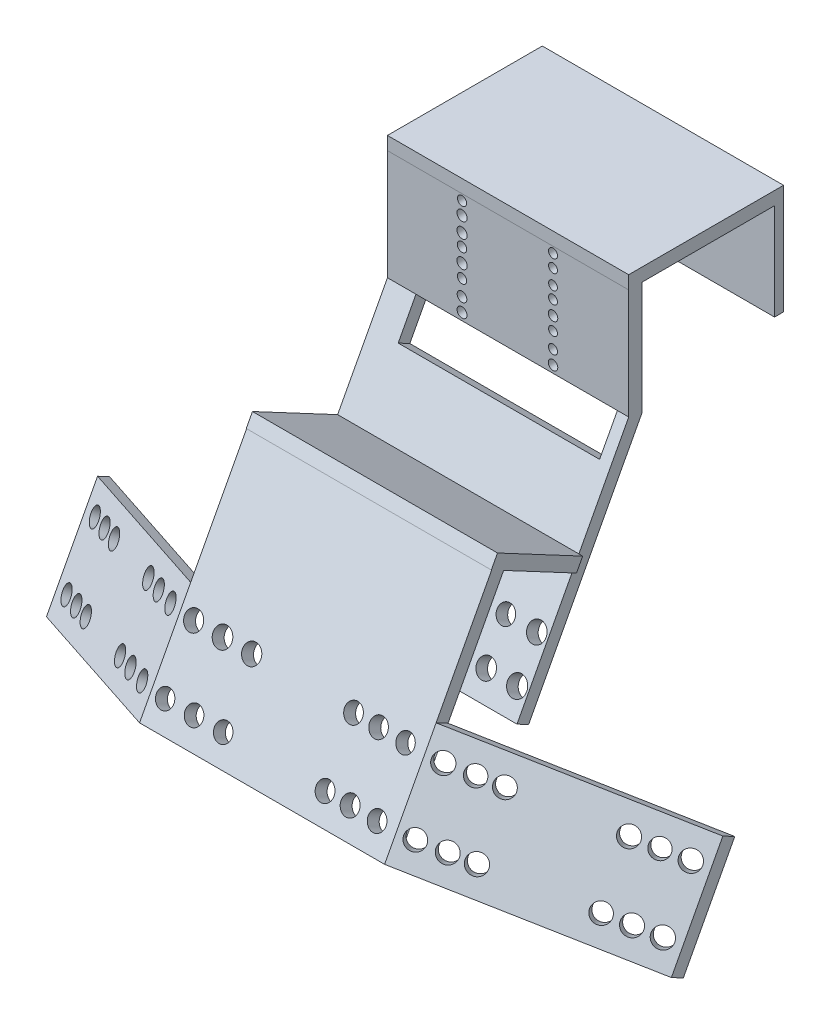
SolidWorks part; units mm, degrees
ref_plane "Plan de face" through (0, 0, 0) normal (0, 0, 1) x (1, 0, 0)
ref_plane "Plan de dessus" through (0, 0, 0) normal (0, 1, 0) x (1, 0, 0)
ref_plane "Plan de droite" through (0, 0, 0) normal (1, 0, 0) x (0, 0, -1)
sketch "Esquisse1" plane through (0, 0, 0) normal (0, 0, 1) x (1, 0, 0)
  line L1 (-52.422, 30.1085) -> (2.578, 30.1085)
  line L2 (-52.422, 30.1085) -> (-52.422, 4.2593)
  line L3 (-52.422, 4.2593) -> (2.578, 4.2593)
  line L4 (2.578, 30.1085) -> (2.578, 4.2593)
extrude "Boss.-Extru.1" add sketch "Esquisse1" along normal blind 3
ref_plane "Plan1" through (0, 0.9388, 1.7655) normal (0, -0.4695, -0.8829) x (1, 0, 0)
sketch "Esquisse2" plane through (0, 0.9388, 1.7655) normal (0, -0.4695, -0.8829) x (1, 0, 0)
  line L1 (-52.422, -3.7607) -> (2.578, -3.7607)
  line L2 (-52.422, -3.7607) -> (-52.422, 51.2393)
  line L3 (-52.422, 51.2393) -> (2.578, 51.2393)
  line L4 (2.578, -3.7607) -> (2.578, 51.2393)
  dimension "D1" = 55
extrude "Boss.-Extru.2" add sketch "Esquisse2" against normal blind 3
ref_plane "Plan12" through (0, 30.1085, 0) normal (0, 1, 0) x (1, 0, 0)
sketch "Esquisse16" plane through (0, 30.1085, 0) normal (0, 1, 0) x (1, 0, 0)
  line L0 (-52.422, -3) -> (-52.422, 0) construction
  line L1 (-52.422, -3.0047) -> (2.578, -3.0047)
  line L2 (-52.422, -3.0047) -> (-52.422, 32.3024)
  line L3 (-52.422, 32.3024) -> (2.578, 32.3024)
  line L4 (2.578, -3.0047) -> (2.578, 32.3024)
extrude "Boss.-Extru.15" add sketch "Esquisse16" along normal blind 3
sketch "Esquisse19" plane through (0, 0.9388, 1.7655) normal (0, -0.4695, -0.8829) x (1, 0, 0)
  line L0 (-51.2999, 51.5904) -> (-51.2999, 21.0995)
ref_plane "Plan15" through (0, 2.3472, 4.4144) normal (0, 0.4695, 0.8829) x (1, 0, 0)
sketch "Esquisse20" plane through (0, 2.3472, 4.4144) normal (0, 0.4695, 0.8829) x (1, 0, 0)
  line L0 (-52.422, -21.1686) -> (2.578, -21.1686)
  line L1 (-52.422, -51.2393) -> (-52.422, 3.0127) construction
  line L2 (2.578, 3.0127) -> (2.578, -51.2393) construction
ref_plane "Plan16" through (0, -18.6908, 9.9381) normal (0, -0.8829, 0.4695) x (1, 0, 0)
sketch "Esquisse21" plane through (0, -18.6908, 9.9381) normal (0, -0.8829, 0.4695) x (1, 0, 0)
  line L1 (-52.422, 4.9996) -> (3.4425, 4.9996)
  line L2 (-52.422, 4.9996) -> (-52.422, 26.9996)
  line L3 (-52.422, 26.9996) -> (3.4425, 26.9996)
  line L4 (3.4425, 4.9996) -> (3.4425, 26.9996)
  dimension "D1" = 22
extrude "Boss.-Extru.17" add sketch "Esquisse21" along normal blind 3
ref_plane "Plan17" through (0, 12.6755, 23.8392) normal (0, 0.4695, 0.8829) x (1, 0, 0)
sketch "Esquisse25" plane through (0, 2.3472, 4.4144) normal (0, 0.4695, 0.8829) x (1, 0, 0)
  line L1 (0, 3.4498) -> (-45.9174, 3.4498)
  line L2 (0, 3.4498) -> (0, -5.6233)
  line L3 (0, -5.6233) -> (-45.9174, -5.6233)
  line L4 (-45.9174, 3.4498) -> (-45.9174, -5.6233)
extrude "Enlèv. mat.-Extru.1" cut sketch "Esquisse25" against normal blind 16
sketch "Esquisse45" plane through (0, 12.6755, 23.8392) normal (0, 0.4695, 0.8829) x (1, 0, 0)
  circle A0 centre (-49.258, -56.656) radius 2.0726
  circle A1 centre (-42.6707, -56.656) radius 2.13
  circle A2 centre (-36.0232, -56.656) radius 2.0885
  circle A3 centre (-30.2676, -56.656) radius 2.0509
  circle A4 centre (-24.6851, -56.656) radius 2.0081
  circle A5 centre (-18.6774, -56.656) radius 2.0845
  circle A6 centre (-12.8051, -56.656) radius 2.0368
  circle A7 centre (-7.0871, -56.656) radius 2.025
  circle A8 centre (-0.9439, -56.656) radius 2.0074
  circle A9 centre (-49.258, -70.4739) radius 2.0023
  circle A10 centre (-42.6707, -70.4739) radius 2.0258
  circle A11 centre (-36.0232, -70.4739) radius 2.0174
  circle A12 centre (-30.2676, -70.4739) radius 2.096
  circle A13 centre (-24.6851, -70.4739) radius 2.0606
  circle A14 centre (-18.6774, -70.4739) radius 2.057
  circle A15 centre (-12.8051, -70.4739) radius 2.0521
  circle A16 centre (-7.0871, -70.4739) radius 2.0593
  circle A17 centre (-0.9439, -70.4739) radius 2.033
sketch "Esquisse47" plane through (0, 0.9388, 1.7655) normal (0, -0.4695, -0.8829) x (1, 0, 0)
  circle A0 centre (0, 36.1252) radius 2.1201
  circle A1 centre (-7.0557, 36.1252) radius 2.016
  circle A2 centre (-15.5678, 36.1252) radius 2.2443
  circle A3 centre (-23.2377, 36.1252) radius 2.0254
  circle A4 centre (-29.4141, 36.1252) radius 2.0106
  circle A5 centre (-36.0059, 36.1252) radius 2.1761
  circle A6 centre (-42.5865, 36.1252) radius 2.0604
  circle A7 centre (-49.1784, 36.1252) radius 2.0528
  circle A8 centre (0, 45.6601) radius 2.1829
  circle A9 centre (-7.0557, 45.6601) radius 2.1219
  circle A10 centre (-15.5678, 45.6601) radius 2.0143
  circle A11 centre (-23.2377, 45.6601) radius 2.112
  circle A12 centre (-29.4141, 45.6601) radius 2.1822
  circle A13 centre (-36.0059, 45.6601) radius 2.1908
  circle A14 centre (-42.5865, 45.6601) radius 2.0165
  circle A15 centre (-49.1784, 45.6601) radius 2.0312
extrude "Enlèv. mat.-Extru.14" cut sketch "Esquisse47" against normal blind 10
sketch "Esquisse48" plane through (0, 30.1085, 0) normal (0, 1, 0) x (1, 0, 0)
  line L1 (-52.422, 32.3024) -> (-52.422, 0) construction
  line L2 (2.578, 32.3024) -> (-52.422, 32.3024)
  line L3 (2.578, 32.3024) -> (2.578, 30.2544)
  line L4 (2.578, 30.2544) -> (-52.422, 30.2544)
  line L5 (-52.422, 32.3024) -> (-52.422, 30.2544)
extrude "Boss.-Extru.21" add sketch "Esquisse48" against normal blind 22
sketch "Esquisse63" plane through (0, -18.6908, 9.9381) normal (0, -0.8829, 0.4695) x (1, 0, 0)
  line L0 (-52.422, 26.9996) -> (-52.422, 4.9996) construction
  line L1 (-52.422, 23.8167) -> (-52.422, 26.902)
  line L4 (3.4425, 26.902) -> (3.4425, 23.8167)
  line L5 (3.4425, 4.9996) -> (3.4425, 26.9996) construction
  line L6 (3.4425, 23.8167) -> (46.7437, -1.1833)
  line L7 (3.4425, 26.902) -> (46.7437, 1.902)
  line L8 (46.7437, -1.1833) -> (46.7437, 1.902)
  line L9 (-52.422, 23.8167) -> (-95.7233, -1.1833)
  line L10 (-52.422, 26.902) -> (-95.7233, 1.902)
  line L11 (-95.7233, -1.1833) -> (-95.7233, 1.902)
extrude "Boss.-Extru.22" add sketch "Esquisse63" along normal blind 55
sketch "Esquisse64" plane through (0, -18.6908, 9.9381) normal (0, -0.8829, 0.4695) x (1, 0, 0)
  line L0 (-52.422, 26.902) -> (-95.7233, 1.902) construction
  line L1 (3.4425, 23.8167) -> (-52.422, 23.8167)
  line L2 (3.4425, 23.8167) -> (3.4425, 26.902)
  line L3 (3.4425, 26.902) -> (-52.422, 26.902)
  line L4 (-52.422, 23.8167) -> (-52.422, 26.902)
extrude "Boss.-Extru.24" add sketch "Esquisse64" along normal blind 55
ref_plane "Plan19" through (11.1736, 9.0858, 17.0878) normal (-0.5, -0.4066, -0.7647) x (-0.866, 0.2347, 0.4415)
sketch "Esquisse66" plane through (11.1736, 9.0858, 17.0878) normal (-0.5, -0.4066, -0.7647) x (-0.866, 0.2347, 0.4415)
  line L0 (8.9271, -76.1686) -> (8.9271, -24.1686) construction
  line L1 (-41.0729, -21.1686) -> (8.9271, -21.1686)
  line L2 (-41.0729, -21.1686) -> (-41.0729, -51.1686)
  line L3 (-41.0729, -51.1686) -> (8.9271, -51.1686)
  line L4 (8.9271, -21.1686) -> (8.9271, -51.1686)
  line L5 (8.9271, -76.1686) -> (-41.0729, -76.1686) construction
  point P7 (-16.0729, -51.1686)
  point P10 (-16.0729, -76.1686)
  dimension "D1" = 25
extrude "Enlèv. mat.-Extru.15" cut sketch "Esquisse66" against normal blind 55
ref_plane "Plan20" through (-23.4185, 19.0427, 35.8141) normal (0.5, -0.4066, -0.7647) x (-0.866, -0.2347, -0.4415)
sketch "Esquisse67" plane through (-23.4185, 19.0427, 35.8141) normal (0.5, -0.4066, -0.7647) x (-0.866, -0.2347, -0.4415)
  line L0 (33.4904, -76.1686) -> (33.4904, -24.1686) construction
  line L1 (83.4904, -21.1686) -> (33.4904, -21.1686)
  line L2 (83.4904, -21.1686) -> (83.4904, -51.1686)
  line L3 (83.4904, -51.1686) -> (33.4904, -51.1686)
  line L4 (33.4904, -21.1686) -> (33.4904, -51.1686)
  line L5 (83.4904, -76.1686) -> (33.4904, -76.1686) construction
  dimension "D1" = 25
extrude "Enlèv. mat.-Extru.16" cut sketch "Esquisse67" against normal blind 55
sketch "Esquisse68" plane through (0, 12.6755, 23.8392) normal (0, 0.4695, 0.8829) x (1, 0, 0)
  line L1 (3.4425, -21.1686) -> (103.4425, -21.1686)
  line L2 (3.4425, -21.1686) -> (3.4425, -51.17)
  line L3 (3.4425, -51.17) -> (103.4425, -51.17)
  line L4 (103.4425, -21.1686) -> (103.4425, -51.17)
  dimension "D1" = 100
extrude "Enlèv. mat.-Extru.22" cut sketch "Esquisse68" against normal blind 32
sketch "Esquisse70" plane through (0, 12.6755, 23.8392) normal (0, 0.4695, 0.8829) x (1, 0, 0)
  line L1 (-52.422, -21.1686) -> (-113.5545, -21.1686)
  line L2 (-52.422, -21.1686) -> (-52.422, -51.2476)
  line L3 (-52.422, -51.2476) -> (-113.5545, -51.2476)
  line L4 (-113.5545, -21.1686) -> (-113.5545, -51.2476)
extrude "Enlèv. mat.-Extru.28" cut sketch "Esquisse45" against normal blind 42 contours A7 | A6 | A2 | A1 | A0 | A9 | A10 | A11 | A15 | A8 | A16 | A17
sketch "Esquisse72" plane through (11.1736, 9.0858, 17.0878) normal (-0.5, -0.4066, -0.7647) x (-0.866, 0.2347, 0.4415)
  circle A0 centre (7.1427, -56.9402) radius 2.0721
  circle A1 centre (1.4989, -56.9402) radius 2.0079
  circle A2 centre (-3.598, -56.9402) radius 2.0397
  circle A3 centre (-36.0141, -56.9402) radius 2.0886
  circle A4 centre (-30.6394, -56.9402) radius 2.0005
  circle A5 centre (-25.2467, -56.9402) radius 2.0614
  circle A6 centre (7.1427, -70.5076) radius 2.0267
  circle A7 centre (1.4989, -70.5076) radius 2.0484
  circle A8 centre (-3.598, -70.5076) radius 2.0741
  circle A9 centre (-25.2467, -70.5076) radius 2.0237
  circle A10 centre (-30.6394, -70.5076) radius 2.0536
  circle A11 centre (-36.0141, -70.5076) radius 2.0782
extrude "Enlèv. mat.-Extru.29" cut sketch "Esquisse72" against normal blind 42
sketch "Esquisse73" plane through (-23.4185, 19.0427, 35.8141) normal (0.5, -0.4066, -0.7647) x (-0.866, -0.2347, -0.4415)
  circle A0 centre (77.3693, -56.8296) radius 1.9971
  circle A1 centre (72.1513, -56.8296) radius 2.0037
  circle A2 centre (67.0276, -56.8296) radius 2.0387
  circle A3 centre (36.7514, -56.8296) radius 2.033
  circle A4 centre (43.0267, -56.8296) radius 2.0123
  circle A5 centre (48.6135, -56.8296) radius 2.0653
  circle A6 centre (77.3693, -70.5609) radius 2.0122
  circle A7 centre (72.1513, -70.5609) radius 2.0464
  circle A8 centre (67.0276, -70.5609) radius 2.0366
  circle A9 centre (48.6135, -70.5609) radius 2.0102
  circle A10 centre (43.0267, -70.5609) radius 2.0496
  circle A11 centre (36.7514, -70.5609) radius 2.0308
extrude "Enlèv. mat.-Extru.30" cut sketch "Esquisse73" against normal blind 42
sketch "Esquisse74" plane through (0, 0, 0) normal (0, 0, 1) x (1, 0, 0)
  circle A0 centre (-35.422, 28.7163) radius 1.0473
  circle A1 centre (-35.422, 6.6615) radius 1.1278
  circle A2 centre (-35.422, 25.7985) radius 1.1592
  circle A3 centre (-35.422, 22.3764) radius 1.1695
  circle A4 centre (-35.422, 9.764) radius 1.102
  circle A5 centre (-35.422, 13.365) radius 1.0676
  circle A6 centre (-35.422, 19.597) radius 1.0763
  circle A7 centre (-35.422, 16.3847) radius 1.179
  circle A8 centre (-14.6759, 28.7163) radius 1.0238
  circle A9 centre (-14.6759, 25.7985) radius 1.0163
  circle A10 centre (-14.6759, 22.3764) radius 1.0055
  circle A11 centre (-14.6759, 19.597) radius 1.0078
  circle A12 centre (-14.6759, 16.3847) radius 1.0853
  circle A13 centre (-14.6759, 13.365) radius 1.0066
  circle A14 centre (-14.6759, 9.764) radius 1.0324
  circle A15 centre (-14.6759, 6.6615) radius 1.0854
extrude "Enlèv. mat.-Extru.31" cut sketch "Esquisse74" along normal blind 25
sketch "Esquisse75" plane through (0, 12.6755, 23.8392) normal (0, 0.4695, 0.8829) x (1, 0, 0)
  line L1 (-52.422, -21.1686) -> (-107.1908, -21.1686)
  line L2 (-52.422, -21.1686) -> (-52.422, -51.3402)
  line L3 (-52.422, -51.3402) -> (-107.1908, -51.3402)
  line L4 (-107.1908, -21.1686) -> (-107.1908, -51.3402)
extrude "Enlèv. mat.-Extru.32" cut sketch "Esquisse75" against normal blind 33
ref_plane "Plan5" through (0, -25.1341, 17.5991) normal (0, 0.8192, -0.5736) x (-1, 0, 0)
sketch "Esquisse8" plane through (0, -25.1341, 17.5991) normal (0, 0.8192, -0.5736) x (-1, 0, 0)
  line L1 (-3.0624, 5.3899) -> (51.888, 5.3899)
  line L2 (-3.0624, 5.3899) -> (-3.0624, 24.984)
  line L3 (-3.0624, 24.984) -> (51.888, 24.984)
  line L4 (51.888, 5.3899) -> (51.888, 24.984)
